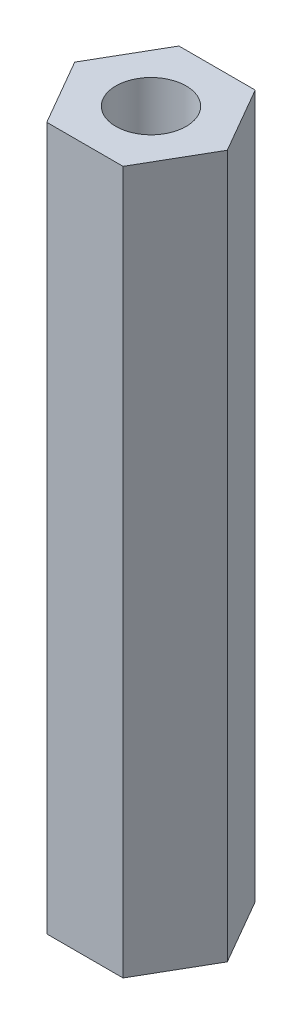
SolidWorks part; units mm, degrees
material "Brass"
ref_plane "Front Plane" through (0, 0, 0) normal (0, 0, 1) x (1, 0, 0)
ref_plane "Top Plane" through (0, 0, 0) normal (0, 1, 0) x (1, 0, 0)
ref_plane "Right Plane" through (0, 0, 0) normal (1, 0, 0) x (0, 0, -1)
sketch "Sketch1" plane through (0, 0, 0) normal (0, 1, 0) x (1, 0, 0)
  line L1 (1.3568, 2.35) -> (-1.3568, 2.35)
  line L2 (-1.3568, 2.35) -> (-2.7135, 0)
  line L3 (-2.7135, 0) -> (-1.3568, -2.35)
  line L4 (-1.3568, -2.35) -> (1.3568, -2.35)
  line L5 (1.3568, -2.35) -> (2.7135, 0)
  line L6 (2.7135, 0) -> (1.3568, 2.35)
  circle A0 centre (0, 0) radius 2.35 construction
  dimension "D1" = 4.7
extrude "Boss-Extrude1" add sketch "Sketch1" along normal mid plane 25
sketch "Sketch3" plane through (0, 12.5, 0) normal (0, 1, 0) x (1, 0, 0)
  circle A0 centre (0, 0) radius 1.25
  dimension "D1" = 2.5
extrude "Cut-Extrude1" cut sketch "Sketch3" against normal blind 7 contours A0
mirror "Mirror1" about plane through (0, 0, 0) normal (0, 1, 0) of "Cut-Extrude1"
